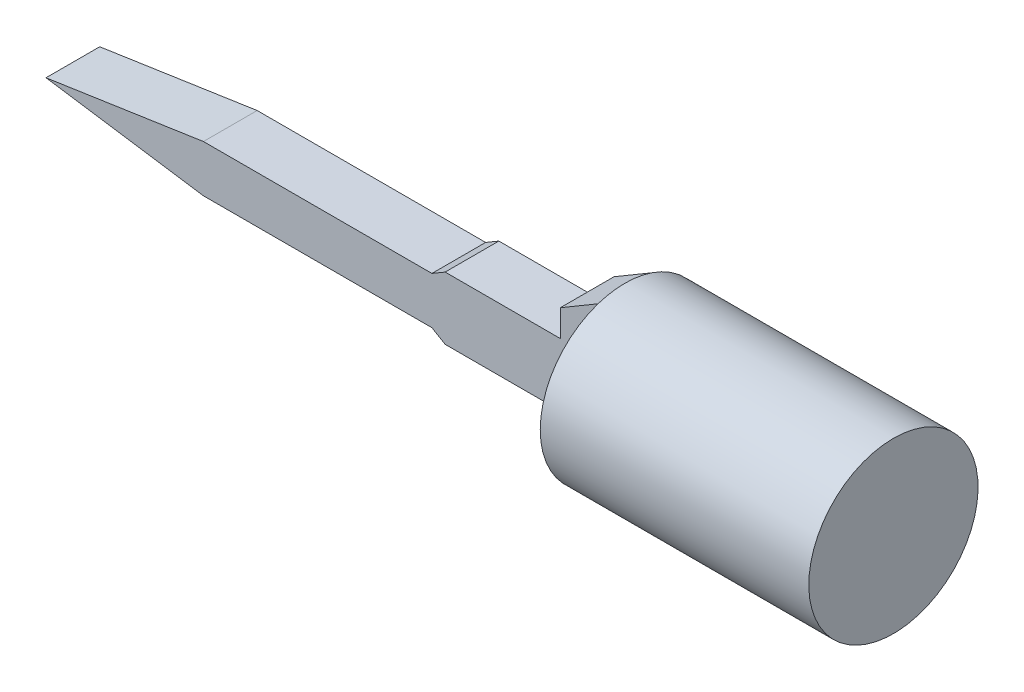
SolidWorks part; units mm, degrees
ref_plane "Front Plane" through (0, 0, 0) normal (0, 0, 1) x (1, 0, 0)
ref_plane "Top Plane" through (0, 0, 0) normal (0, 1, 0) x (1, 0, 0)
ref_plane "Right Plane" through (0, 0, 0) normal (1, 0, 0) x (0, 0, -1)
sketch "Sketch1" plane through (0, 0, 0) normal (0, 0, 1) x (1, 0, 0)
  line L1 (-60, 0) -> (-74.0364, -8.2854)
  line L2 (-74.0364, -8.2854) -> (-74.0364, -18.2278)
  line L3 (-74.0364, -18.2278) -> (-116.9254, -18.2278)
  line L4 (-116.9254, -18.2278) -> (-121.846, -21.1324)
  line L5 (-121.846, -21.1324) -> (-206.9254, -21.1324)
  line L6 (-74.0364, -18.2278) -> (-74.0364, -41.5442)
  line L7 (-121.846, -38.6396) -> (-206.9254, -38.6396)
  line L8 (-116.9254, -41.5442) -> (-121.846, -38.6396)
  line L9 (-74.0364, -41.5442) -> (-116.9254, -41.5442)
  line L10 (-74.0364, -51.4866) -> (-74.0364, -41.5442)
  line L11 (-60, -59.772) -> (-74.0364, -51.4866)
  line L15 (-74.0364, -18.2278) -> (-74.0364, -41.5442)
  line L16 (-60, 0) -> (-60, -59.772)
  line L17 (-60, -29.886) -> (-265.5564, -29.886) construction
  line L18 (-265.5564, -29.886) -> (-206.9254, -21.1324)
  line L19 (-265.5564, -29.886) -> (-206.9254, -38.6396)
  dimension "D2" = 90
extrude "Boss-Extrude7" add sketch "Sketch1" along normal blind 20 contours L15 L17 L19 L7 L8 L9 | L17 L6 L3 L4 L5 L18 | L16 L17 L15 L10 L11 | L17 L16 L1 L2 L6
sketch "Sketch12" plane through (-60, 0, 0) normal (1, 0, 0) x (0, 0, -1)
  line L0 (-10, 0) -> (-10, -59.772) construction
  line L1 (-20, 0) -> (0, 0) construction
  line L2 (-20, -59.772) -> (0, -59.772) construction
  circle A0 centre (-10, -29.886) radius 31.5146
extrude "Boss-Extrude8" add sketch "Sketch12" along normal blind 100
